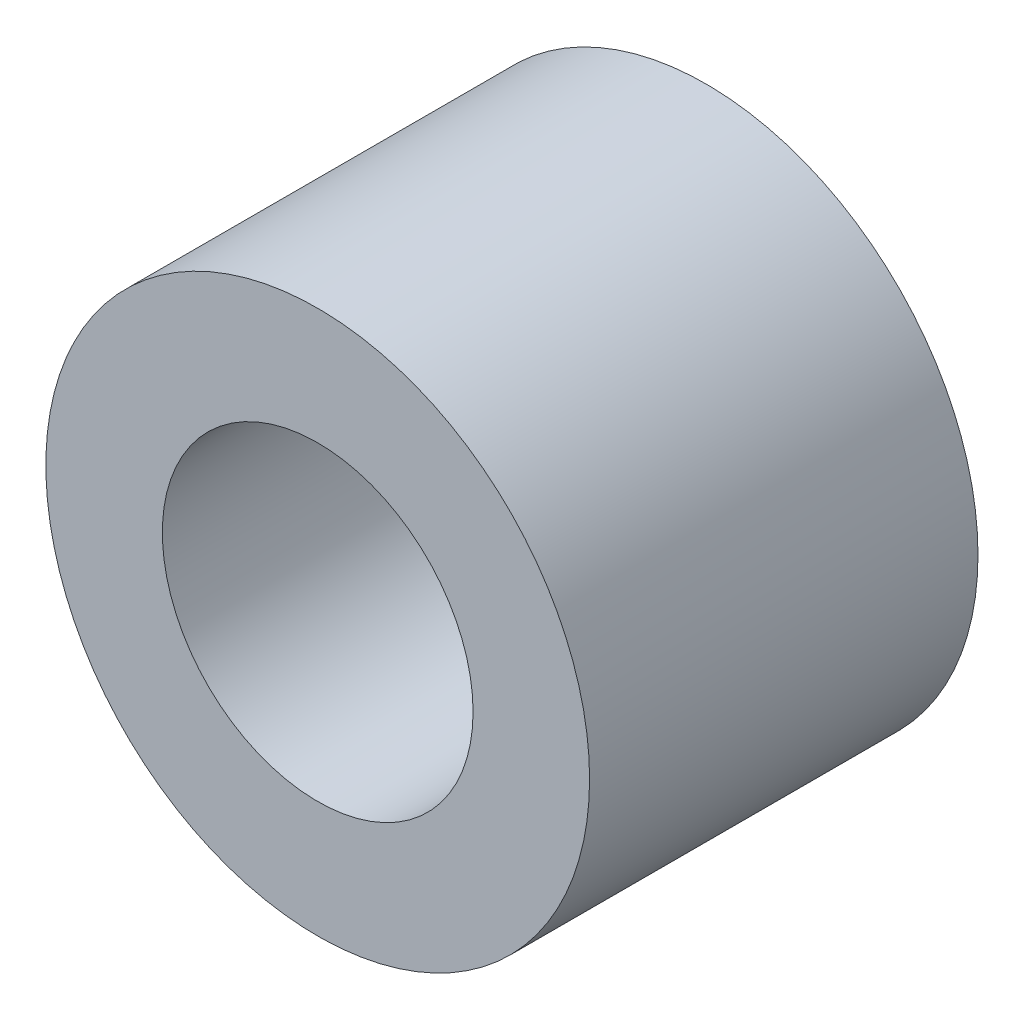
SolidWorks part; units mm, degrees
ref_plane "前视基准面" through (0, 0, 0) normal (0, 0, 1) x (1, 0, 0)
ref_plane "上视基准面" through (0, 0, 0) normal (0, 1, 0) x (1, 0, 0)
ref_plane "右视基准面" through (0, 0, 0) normal (1, 0, 0) x (0, 0, -1)
sketch "草图1" plane through (0, 0, 0) normal (0, 0, 1) x (1, 0, 0)
  circle A0 centre (0, 0) radius 7
  circle A1 centre (0, 0) radius 4
extrude "凸台-拉伸1" add sketch "草图1" along normal blind 10
